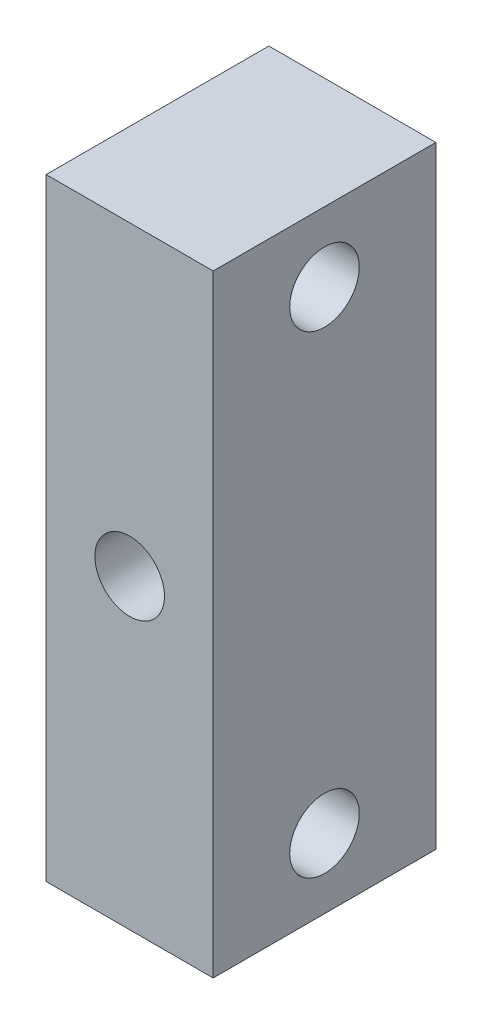
SolidWorks part; units mm, degrees
ref_plane "前视基准面" through (0, 0, 0) normal (0, 0, 1) x (1, 0, 0)
ref_plane "上视基准面" through (0, 0, 0) normal (0, 1, 0) x (1, 0, 0)
ref_plane "右视基准面" through (0, 0, 0) normal (1, 0, 0) x (0, 0, -1)
sketch "草图1" plane through (0, 0, 0) normal (0, 1, 0) x (1, 0, 0)
  line L1 (-3, 4) -> (3, 4)
  line L2 (-3, 4) -> (-3, -4)
  line L3 (-3, -4) -> (3, -4)
  line L4 (3, 4) -> (3, -4)
  line L5 (-3, 4) -> (3, -4) construction
  line L6 (-3, -4) -> (3, 4) construction
  point P0 (0, 0)
  dimension "D1" = 6
  dimension "D2" = 8
extrude "凸台-拉伸1" add sketch "草图1" along normal mid plane 22
sketch "草图2" plane through (0, 0, 4) normal (0, 0, 1) x (1, 0, 0)
  circle A0 centre (0, 0) radius 1.25
  dimension "D1" = 2.5
extrude "切除-拉伸1" cut sketch "草图2" against normal through all
sketch "草图3" plane through (-3, 0, 0) normal (-1, 0, 0) x (0, 0, 1)
  circle A0 centre (0, 8.5) radius 1.25
  circle A1 centre (0, -8.5) radius 1.25
  dimension "D3" = 2.5
  dimension "D1" = 8.5
  dimension "D2" = 8.5
extrude "切除-拉伸2" cut sketch "草图3" against normal through all
